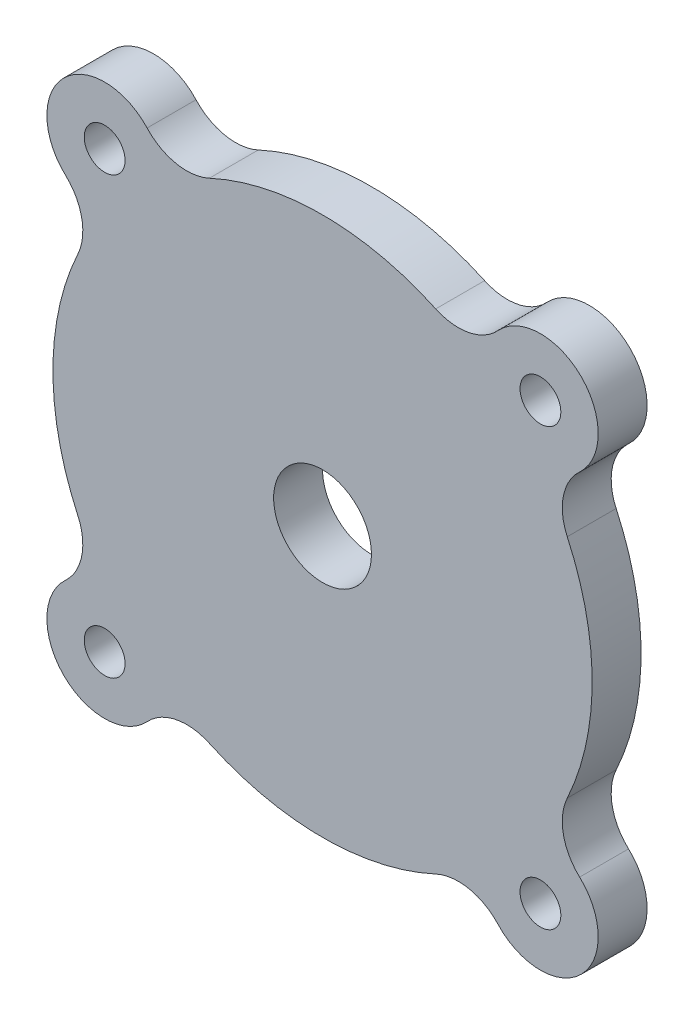
SolidWorks part; units mm, degrees
material "6061 Alloy"
ref_plane "Front Plane" through (0, 0, 0) normal (0, 0, 1) x (1, 0, 0)
ref_plane "Top Plane" through (0, 0, 0) normal (0, 1, 0) x (1, 0, 0)
ref_plane "Right Plane" through (0, 0, 0) normal (1, 0, 0) x (0, 0, -1)
sketch "Sketch1" plane through (0, 0, 0) normal (0, 0, 1) x (1, 0, 0)
  line L1 (-28.2843, -28.2843) -> (28.2843, -28.2843) construction
  line L2 (-28.2843, -28.2843) -> (-28.2843, 28.2843) construction
  line L3 (-28.2843, 28.2843) -> (28.2843, 28.2843) construction
  line L4 (28.2843, -28.2843) -> (28.2843, 28.2843) construction
  line L5 (-28.2843, -28.2843) -> (28.2843, 28.2843) construction
  line L6 (-28.2843, 28.2843) -> (28.2843, -28.2843) construction
  circle A0 centre (0, 0) radius 40 construction
  arc A1 (-20.7853, 28.1597) -> (-28.1597, 20.7853) centre (-28.2843, 28.2843) ccw
  arc A2 (20.7853, 28.1597) -> (28.1597, 20.7853) centre (28.2843, 28.2843) ccw construction
  arc A3 (20.7853, -28.1597) -> (28.1597, -20.7853) centre (28.2843, -28.2843) ccw
  arc A4 (-20.7853, -28.1597) -> (-28.1597, -20.7853) centre (-28.2843, -28.2843) ccw construction
  arc A5 (28.1597, -20.7853) -> (20.7853, -28.1597) centre (28.2843, -28.2843) ccw construction
  arc A6 (-28.1597, -20.7853) -> (-20.7853, -28.1597) centre (-28.2843, -28.2843) ccw
  arc A7 (-28.1597, 20.7853) -> (-20.7853, 28.1597) centre (-28.2843, 28.2843) ccw construction
  arc A8 (28.1597, 20.7853) -> (20.7853, 28.1597) centre (28.2843, 28.2843) ccw
  arc A9 (-20.7853, 28.1597) -> (20.7853, 28.1597) centre (0, 0) cw
  arc A10 (28.1597, 20.7853) -> (28.1597, -20.7853) centre (0, 0) cw
  arc A11 (20.7853, -28.1597) -> (-20.7853, -28.1597) centre (0, 0) cw
  arc A12 (-28.1597, -20.7853) -> (-28.1597, 20.7853) centre (0, 0) cw
  dimension "D1" = 80
  dimension "D2" = 15
  dimension "D3" = 70
extrude "Boss-Extrude1" add sketch "Sketch1" along normal mid plane 6.35
fillet "Fillet1" radius 7 8 edges at (-28.1597, 20.7853, 0) (-28.1597, -20.7853, 0) (-20.7853, -28.1597, 0) (20.7853, -28.1597, 0) (28.1597, -20.7853, 0) (28.1597, 20.7853, 0) (20.7853, 28.1597, 0) (-20.7853, 28.1597, 0)
hole_wizard "M5 Clearance Hole1" positions "Sketch3" profile "Sketch2" hole size "M5" standard "ANSI Metric"
sketch "Sketch3" plane through (0, 0, 3.175) normal (0, 0, 1) x (1, 0, 0)
  point P0 (-28.2843, 28.2843)
  point P3 (28.2843, 28.2843)
  point P6 (28.2843, -28.2843)
  point P9 (-28.2843, -28.2843)
sketch "Sketch2" plane through (-28.2843, 28.2843, 3.175) normal (1, 0, 0) x (0, -1, 0)
  line L0 (0, 0) -> (0, 7.9423)
  line L1 (0, 7.9423) -> (2.65, 6.35)
  line L2 (2.65, 6.35) -> (2.65, 0)
  line L5 (2.65, 0) -> (0, 0)
  line L10 (0, 7.9423) -> (-2.65, 6.35) construction
  line L11 (0, -6.35) -> (0, 107.95) construction
  dimension "Hole Dia." = 5.3
  dimension "Hole Depth" = 6.35
  dimension "Drill Angle" = 118
sketch "Sketch4" plane through (0, 0, 3.175) normal (0, 0, 1) x (1, 0, 0)
  circle A0 centre (0, 0) radius 6.35
  dimension "D1" = 12.7
extrude "Cut-Extrude1" cut sketch "Sketch4" against normal through all
sketch "Sketch5" plane through (0, 0, 3.175) normal (0, 0, 1) x (1, 0, 0)
  line L1 (-17.6777, -17.6777) -> (17.6777, -17.6777) construction
  line L2 (-17.6777, -17.6777) -> (-17.6777, 17.6777) construction
  line L3 (-17.6777, 17.6777) -> (17.6777, 17.6777) construction
  line L4 (17.6777, -17.6777) -> (17.6777, 17.6777) construction
  line L5 (-17.6777, -17.6777) -> (17.6777, 17.6777) construction
  line L6 (-17.6777, 17.6777) -> (17.6777, -17.6777) construction
  line L7 (8.8388, -8.8388) -> (-8.8388, -8.8388) construction
  line L8 (8.8388, -8.8388) -> (8.8388, 8.8388) construction
  line L9 (8.8388, 8.8388) -> (-8.8388, 8.8388) construction
  line L10 (-8.8388, -8.8388) -> (-8.8388, 8.8388) construction
  line L11 (8.8388, -8.8388) -> (-8.8388, 8.8388) construction
  line L12 (8.8388, 8.8388) -> (-8.8388, -8.8388) construction
  circle A0 centre (0, 0) radius 25 construction
  circle A1 centre (0, 0) radius 12.5 construction
  circle A2 centre (-17.6777, 17.6777) radius 2.5
  circle A4 centre (-12.5, 0) radius 2.5
  circle A5 centre (-25, 0) radius 2.5
  point P0 (0, 0)
  dimension "D1" = 50
  dimension "D2" = 25
  dimension "D3" = 5
extrude "M5 tapped holes" [suppressed] cut sketch "Sketch5" against normal through all
pattern_circular "CirPattern1" [suppressed] count 4 over 360
